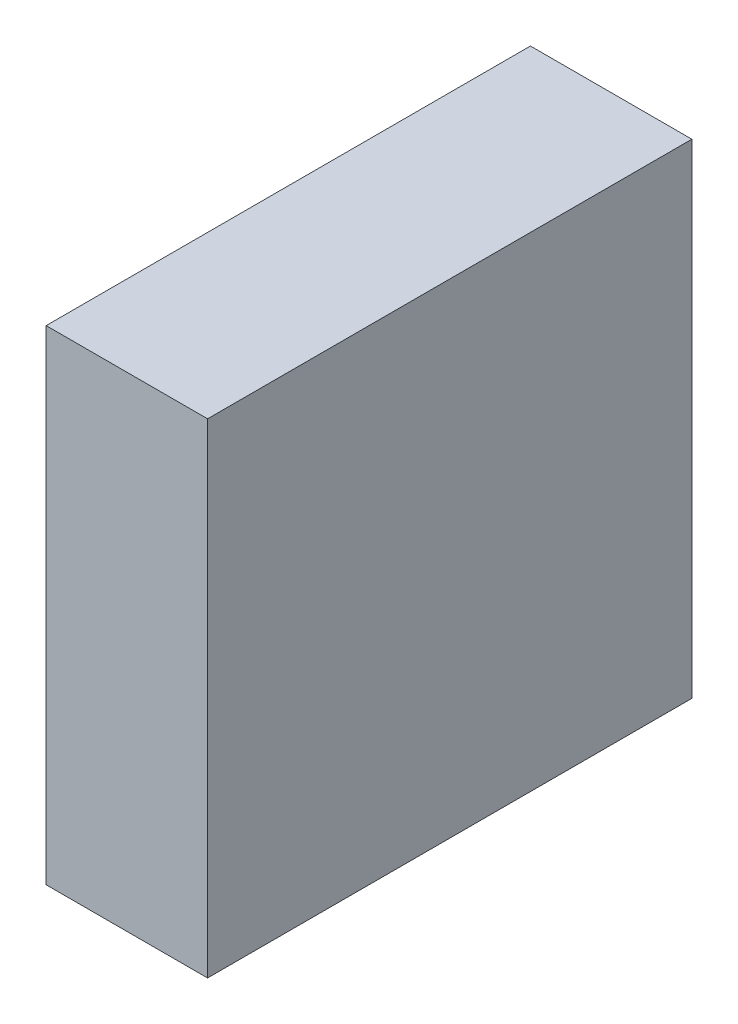
SolidWorks part; units mm, degrees
ref_plane "Front Plane" through (0, 0, 0) normal (0, 0, 1) x (1, 0, 0)
ref_plane "Top Plane" through (0, 0, 0) normal (0, 1, 0) x (1, 0, 0)
ref_plane "Right Plane" through (0, 0, 0) normal (1, 0, 0) x (0, 0, -1)
sketch "Sketch1" plane through (0, 0, 0) normal (0, 0, 1) x (1, 0, 0)
  line L1 (-10, -30) -> (10, -30)
  line L2 (-10, -30) -> (-10, 30)
  line L3 (-10, 30) -> (10, 30)
  line L4 (10, -30) -> (10, 30)
  line L5 (-10, -30) -> (10, 30) construction
  line L6 (-10, 30) -> (10, -30) construction
  point P0 (0, 0)
  dimension "D1" = 60
  dimension "D2" = 20
extrude "Boss-Extrude1" add sketch "Sketch1" along normal mid plane 60
